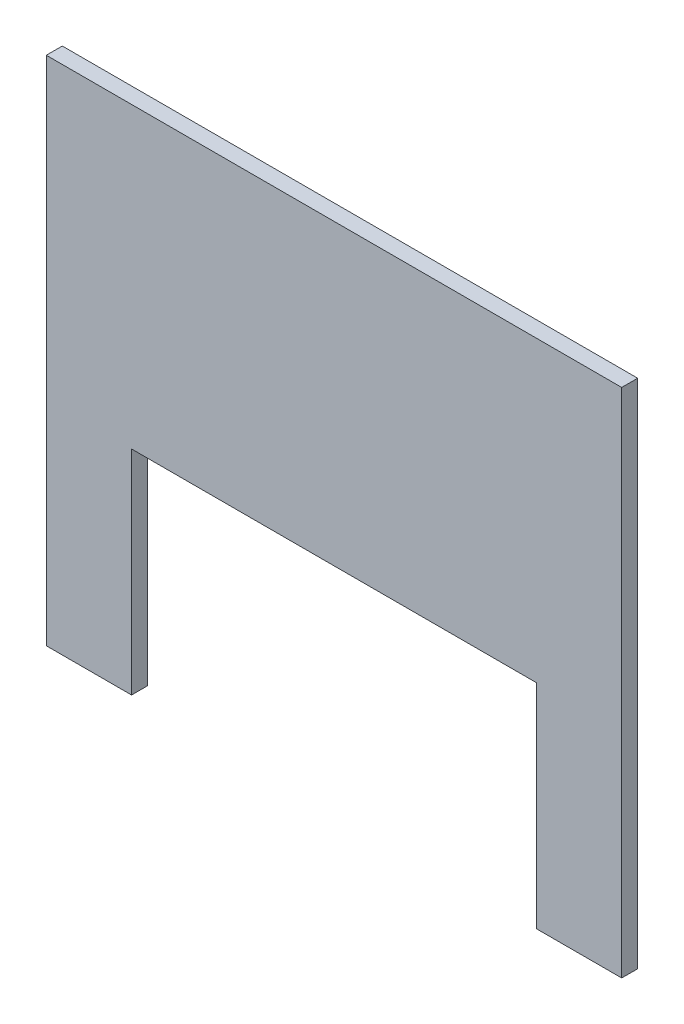
SolidWorks part; units mm, degrees
ref_plane "Front Plane" through (0, 0, 0) normal (0, 0, 1) x (1, 0, 0)
ref_plane "Top Plane" through (0, 0, 0) normal (0, 1, 0) x (1, 0, 0)
ref_plane "Right Plane" through (0, 0, 0) normal (1, 0, 0) x (0, 0, -1)
sketch "Sketch1" plane through (0, 0, 0) normal (0, 0, 1) x (1, 0, 0)
  line L0 (0, 0) -> (25.4, 0)
  line L1 (25.4, 0) -> (25.4, 63.5)
  line L2 (25.4, 63.5) -> (146.05, 63.5)
  line L3 (146.05, 63.5) -> (146.05, 0)
  line L4 (146.05, 0) -> (171.45, 0)
  line L5 (171.45, 0) -> (171.45, 152.4)
  line L6 (171.45, 152.4) -> (0, 152.4)
  line L7 (0, 152.4) -> (0, 0)
  dimension "D1" = 25.4
  dimension "D2" = 63.5
  dimension "D3" = 152.4
  dimension "D4" = 120.65
extrude "Boss-Extrude1" add sketch "Sketch1" along normal blind 4.7625
